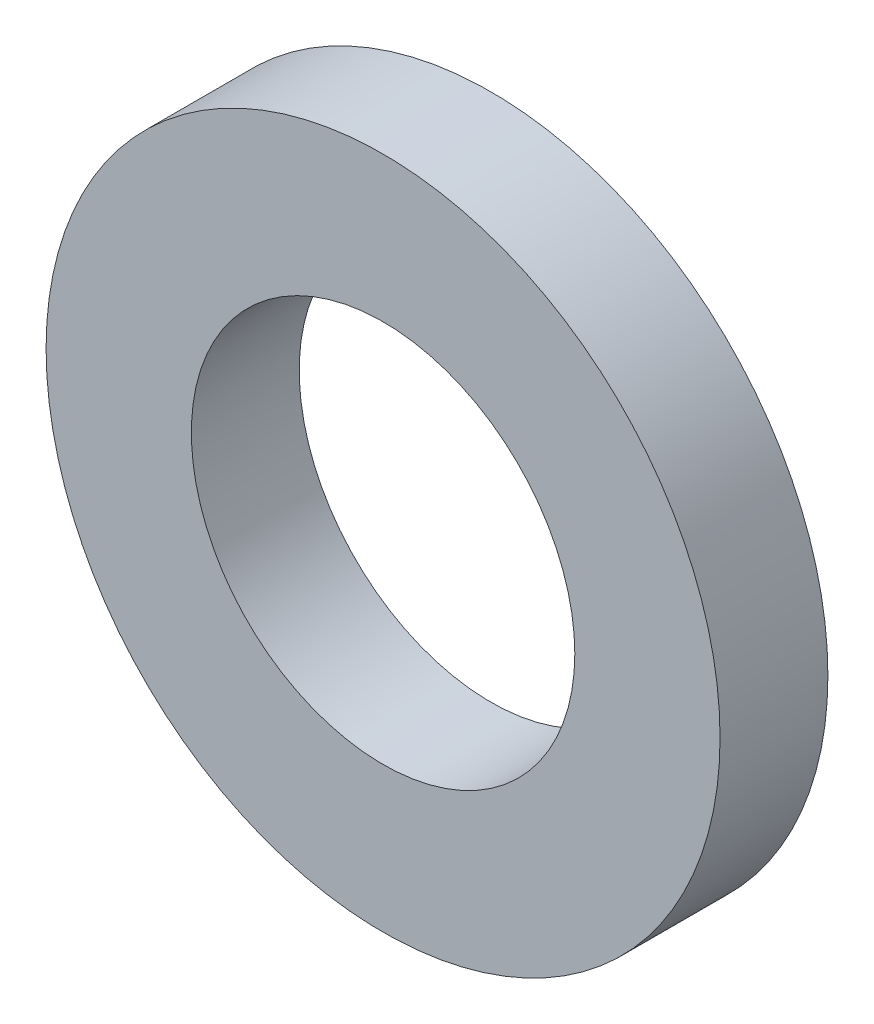
SolidWorks part; units mm, degrees
ref_plane "Front Plane" through (0, 0, 0) normal (0, 0, 1) x (1, 0, 0)
ref_plane "Top Plane" through (0, 0, 0) normal (0, 1, 0) x (1, 0, 0)
ref_plane "Right Plane" through (0, 0, 0) normal (1, 0, 0) x (0, 0, -1)
sketch "Sketch1" plane through (0, 0, 0) normal (0, 0, 1) x (1, 0, 0)
  circle A0 centre (0, 0) radius 1.778
  circle A1 centre (0, 0) radius 3.125
  dimension "D1" = 3.556
  dimension "D2" = 6.25
extrude "Boss-Extrude1" add sketch "Sketch1" along normal blind 1
